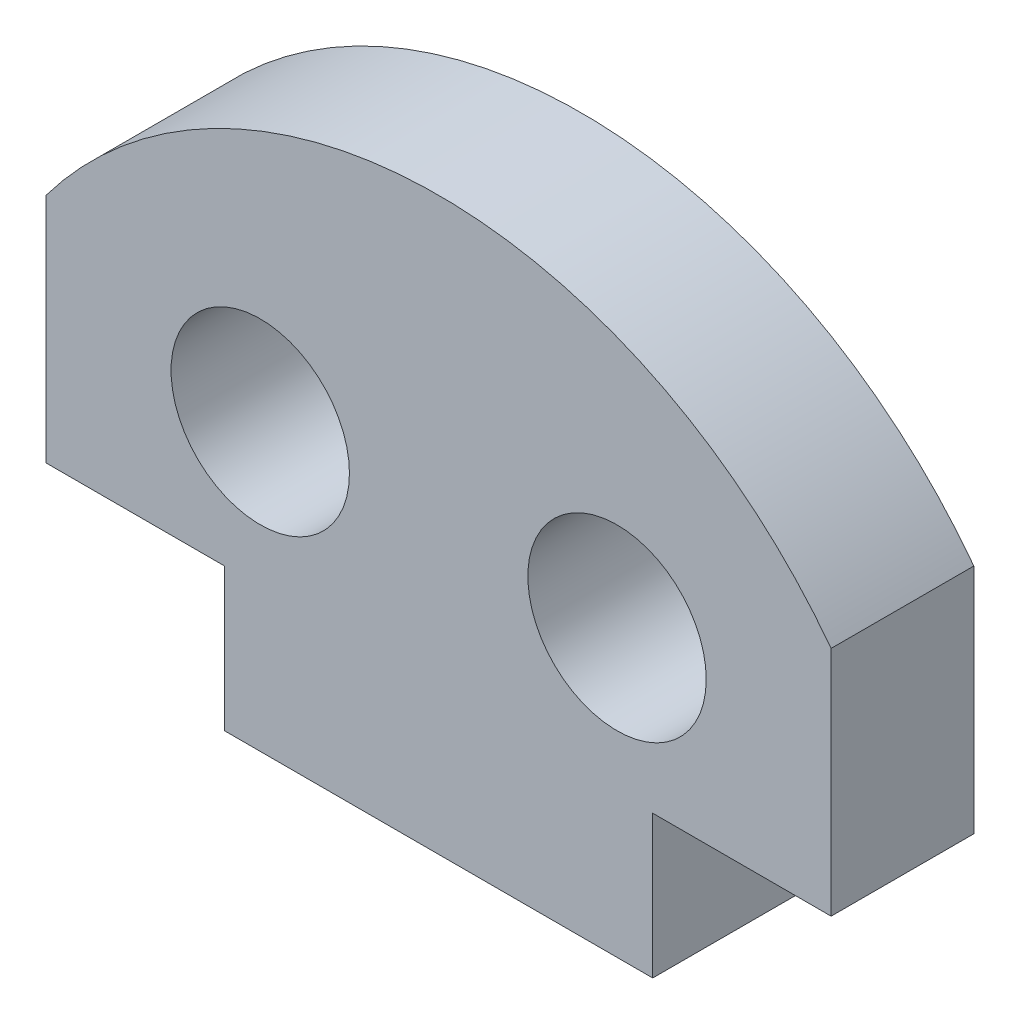
SolidWorks part; units mm, degrees
ref_plane "Front Plane" through (0, 0, 0) normal (0, 0, 1) x (1, 0, 0)
ref_plane "Top Plane" through (0, 0, 0) normal (0, 1, 0) x (1, 0, 0)
ref_plane "Right Plane" through (0, 0, 0) normal (1, 0, 0) x (0, 0, -1)
sketch "Model" plane through (0, 0, 0) normal (0, 0, 1) x (1, 0, 0)
  line L0 (1953.6768, 1458.8841) -> (1951.1768, 1458.8841)
  line L1 (1951.1768, 1458.8841) -> (1951.1768, 1462.1341)
  line L2 (1962.1768, 1458.8841) -> (1962.1768, 1462.1341)
  line L3 (1962.1768, 1458.8841) -> (1959.6768, 1458.8841)
  line L4 (1953.6768, 1458.8841) -> (1953.6768, 1456.8841)
  line L5 (1953.6768, 1456.8841) -> (1959.6768, 1456.8841)
  line L6 (1959.6768, 1456.8841) -> (1959.6768, 1458.8841)
  arc A0 (1962.1768, 1462.1341) -> (1951.1768, 1462.1341) centre (1956.6768, 1458.0091) ccw
  circle A81 centre (1959.1768, 1460.8841) radius 1.25
  circle A82 centre (1954.1768, 1460.8841) radius 1.25
  dimension "D5" = 2.5
  dimension "D6" = 2.5
  dimension "D7" = 6.875
  dimension "D2" = 2.5
  dimension "D3" = 6
  dimension "D4" = 3.25
  dimension "D8" = 3.25
  dimension "D9" = 2
  dimension "D10" = 2.5
  dimension "D11" = 11
extrude "Boss-Extrude1" add sketch "Model" along normal blind 2
